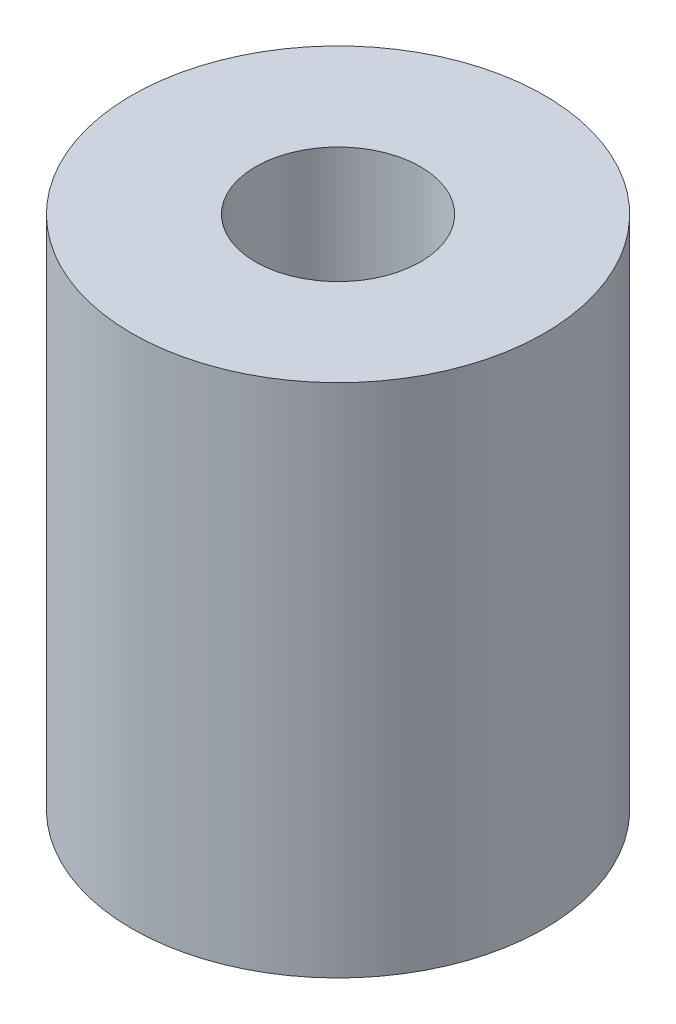
SolidWorks part; units mm, degrees
ref_plane "Front Plane" through (0, 0, 0) normal (0, 0, 1) x (1, 0, 0)
ref_plane "Top Plane" through (0, 0, 0) normal (0, 1, 0) x (1, 0, 0)
ref_plane "Right Plane" through (0, 0, 0) normal (1, 0, 0) x (0, 0, -1)
sketch "Sketch2" plane through (0, 0, 0) normal (0, 1, 0) x (1, 0, 0)
  circle A0 centre (0, 0) radius 4
  circle A1 centre (0, 0) radius 10
  dimension "D1" = 8
  dimension "D2" = 20
extrude "Boss-Extrude1" add sketch "Sketch2" along normal blind 25
